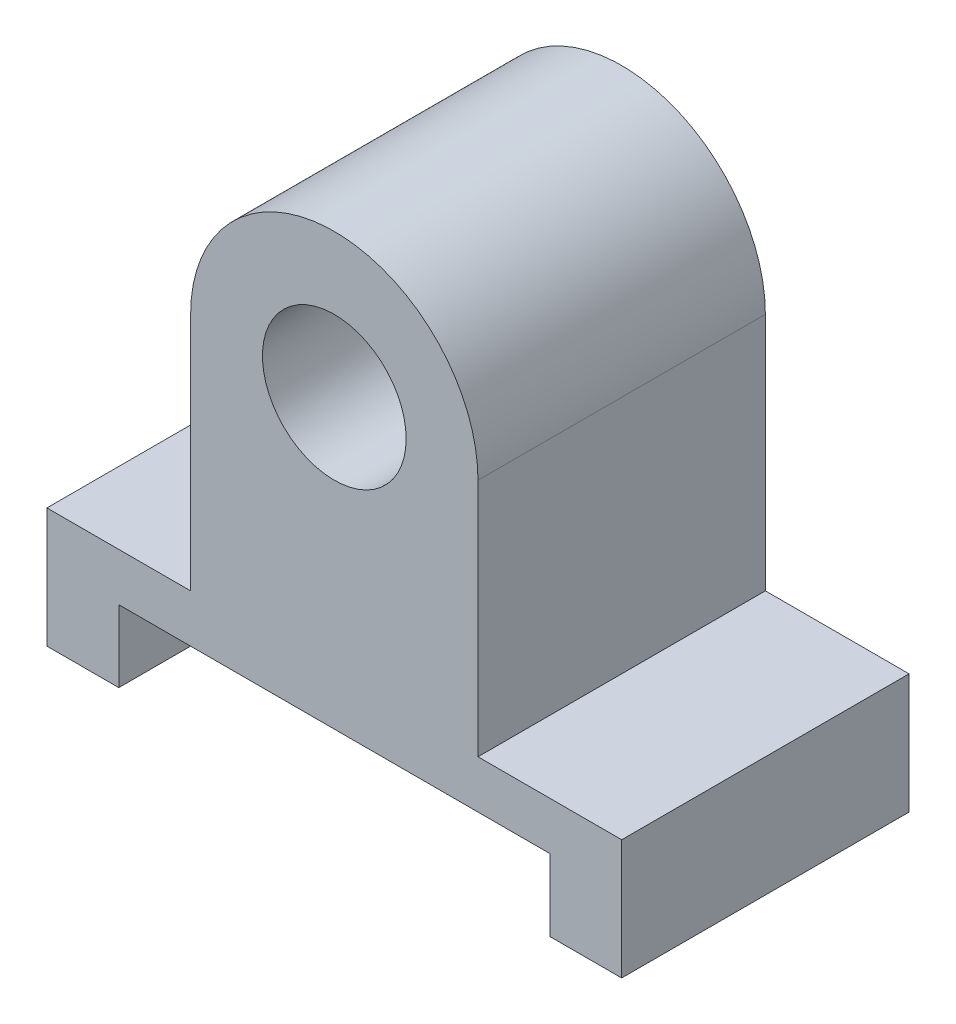
SolidWorks part; units mm, degrees
material "AISI 1020 Steel, Cold Rolled"
ref_plane "Front Plane" through (0, 0, 0) normal (0, 0, 1) x (1, 0, 0)
ref_plane "Top Plane" through (0, 0, 0) normal (0, 1, 0) x (1, 0, 0)
ref_plane "Right Plane" through (0, 0, 0) normal (1, 0, 0) x (0, 0, -1)
sketch "Sketch1" plane through (0, 0, 0) normal (0, 0, 1) x (1, 0, 0)
  line L0 (-27.6024, -21.2881) -> (62.3976, -21.2881)
  line L1 (-27.6024, -21.2881) -> (-27.6024, -36.2881)
  line L2 (62.3976, -21.2881) -> (62.3976, -36.2881)
  line L3 (-27.6024, -36.2881) -> (-42.6024, -36.2881)
  line L4 (62.3976, -36.2881) -> (77.3976, -36.2881)
  line L5 (-42.6024, -36.2881) -> (-42.6024, -11.2881)
  line L6 (77.3976, -36.2881) -> (77.3976, -11.2881)
  line L7 (-42.6024, -11.2881) -> (77.3976, -11.2881) construction
  line L8 (-27.6024, -21.2881) -> (-27.6024, -11.2881) construction
  line L9 (-42.6024, -11.2881) -> (77.3976, -11.2881)
  line L10 (-12.6024, 38.7119) -> (-12.6024, -11.2881)
  line L11 (47.3976, 38.7119) -> (47.3976, -11.2881)
  arc A0 (47.3976, 38.7119) -> (-12.6024, 38.7119) centre (17.3976, 38.7119) ccw
  circle A1 centre (17.3976, 38.7119) radius 15
  point P12 (17.3976, -21.2881)
  dimension "D7" = 50
  dimension "D9" = 30
  dimension "D10" = 30
  dimension "D1" = 90
  dimension "D2" = 15
  dimension "D3" = 15
  dimension "D4" = 15
  dimension "D5" = 15
  dimension "D6" = 25
  dimension "D8" = 50
extrude "Boss-Extrude2" add sketch "Sketch1" along normal blind 60 contours L11 A0 L10 L9 A1 | L9 L5 L3 L1 L0 L2 L4 L6
